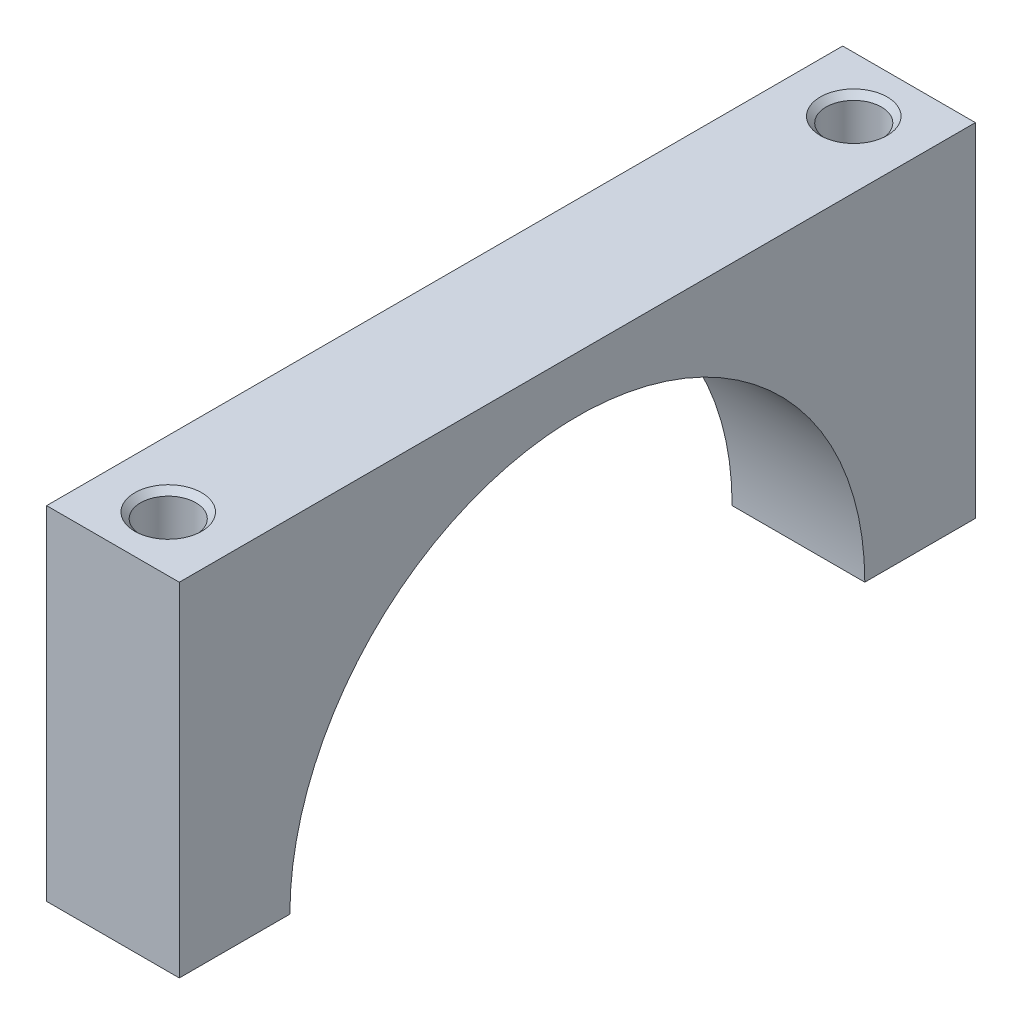
SolidWorks part; units mm, degrees
material "2014 Alloy"
ref_plane "Front Plane" through (0, 0, 0) normal (0, 0, 1) x (1, 0, 0)
ref_plane "Top Plane" through (0, 0, 0) normal (0, 1, 0) x (1, 0, 0)
ref_plane "Right Plane" through (0, 0, 0) normal (1, 0, 0) x (0, 0, -1)
sketch "Sketch1" plane through (0, 0, 0) normal (1, 0, 0) x (0, 0, -1)
  line L0 (-36, 0) -> (36, 0)
  line L1 (36, 0) -> (36, -31)
  line L2 (36, -31) -> (26, -31)
  line L3 (0, 0) -> (0, -31) construction
  line L4 (-36, -31) -> (-26, -31)
  line L5 (-36, 0) -> (-36, -31)
  arc A0 (26, -31) -> (-26, -31) centre (0, -31) ccw
  dimension "D1" = 31
  dimension "D3" = 26
  dimension "D2" = 10
extrude "Boss-Extrude1" add sketch "Sketch1" along normal mid plane 12
hole_wizard "M6 Tapped Hole1" positions "Sketch5" profile "Sketch4" tap size "M6" standard "ISO" end condition through all
sketch "Sketch5" plane through (0, 0, 0) normal (0, 1, 0) x (1, 0, 0)
  line L0 (0, -36) -> (0, -31) construction
  line L1 (6, -36) -> (-6, -36) construction
  line L2 (0, -31) -> (0, 31) construction
  line L3 (0, 31) -> (0, 36) construction
  line L4 (6, 36) -> (-6, 36) construction
  line L5 (0, 36) -> (6, 31) construction
  line L6 (6, 36) -> (6, -36) construction
  line L7 (6, 31) -> (0, 31) construction
  point P0 (0, -31)
  point P2 (0, 31)
  dimension "D1" = 5
sketch "Sketch4" plane through (0, 0, 31) normal (1, 0, 0) x (0, 0, 1)
  line L0 (0, 0) -> (0, 31)
  line L1 (0, 31) -> (2.5, 31)
  line L2 (2.5, 31) -> (2.5, 0.525)
  line L3 (2.5, 0.525) -> (3.025, 0)
  line L5 (3.025, 0) -> (0, 0)
  line L6 (-2.5, 0.525) -> (-3.025, 0) construction
  line L11 (0, -6.35) -> (0, 107.95) construction
  dimension "Thread Major Dia." = 5
  dimension "Thru Tap Drill Depth" = 31
  dimension "Near C'Sink Dia." = 6.05
  dimension "Near C'Sink Angle" = 90
sketch "Sketch6" [suppressed] plane through (-6, 0, 0) normal (-1, 0, 0) x (0, 0, 1)
  line L0 (37, -32) -> (37, 1)
  line L1 (37, 1) -> (-37, 1)
  line L2 (-37, 1) -> (-37, -32)
  line L3 (-37, -32) -> (-24.98, -32)
  line L4 (24.98, -32) -> (37, -32)
  line L5 (36, -31) -> (36, 0)
  line L6 (36, 0) -> (-36, 0)
  line L7 (-36, 0) -> (-36, -31)
  line L8 (-36, -31) -> (-26, -31)
  line L9 (26, -31) -> (36, -31)
  line L10 (36, -31) -> (36, 0) construction
  line L11 (36, 0) -> (-36, 0) construction
  line L12 (-36, 0) -> (-36, -31) construction
  line L13 (-36, -31) -> (-26, -31) construction
  line L14 (26, -31) -> (36, -31) construction
  arc A0 (24.98, -32) -> (-24.98, -32) centre (0, -31) ccw
  arc A1 (26, -31) -> (-26, -31) centre (0, -31) ccw
  arc A2 (26, -31) -> (-26, -31) centre (0, -31) ccw construction
  dimension "D1" = 0
  dimension "D2" = 1
extrude "Boss-Extrude2" [suppressed] add sketch "Sketch6" against normal blind 15
